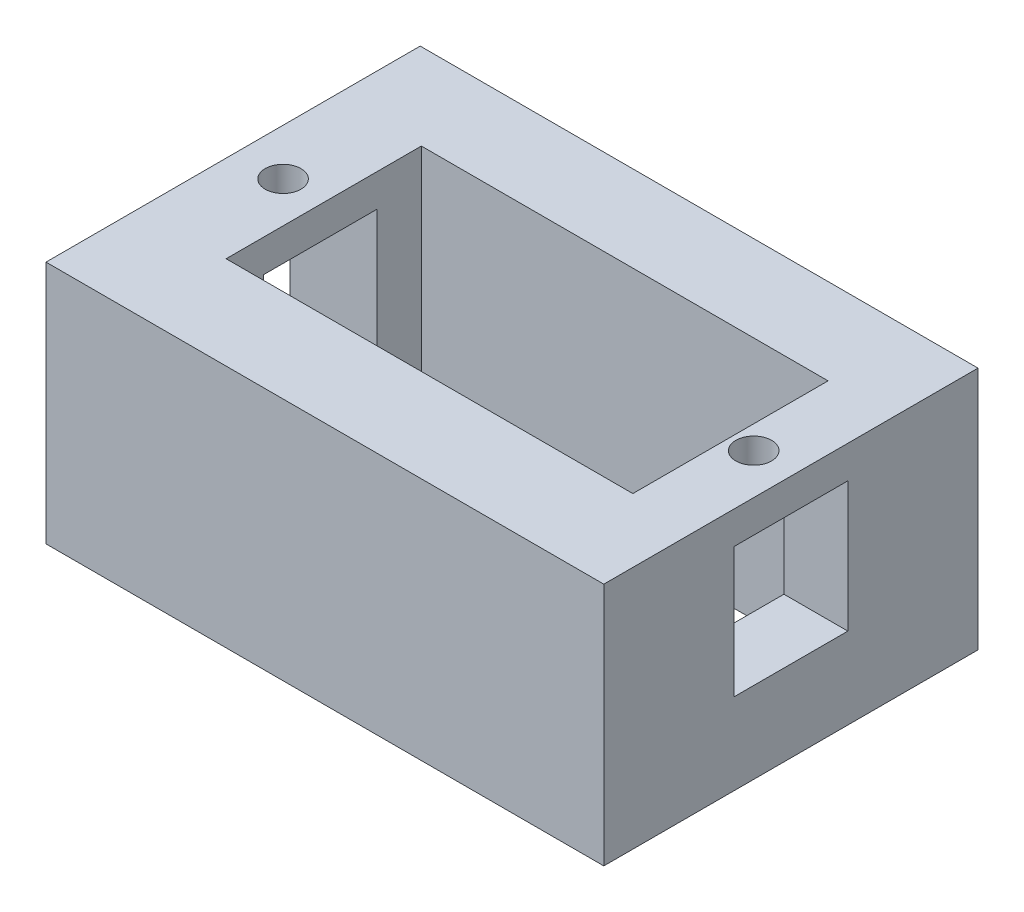
SolidWorks part; units mm, degrees
ref_plane "Plan de face" through (0, 0, 0) normal (0, 0, 1) x (1, 0, 0)
ref_plane "Plan de dessus" through (0, 0, 0) normal (0, 1, 0) x (1, 0, 0)
ref_plane "Plan de droite" through (0, 0, 0) normal (1, 0, 0) x (0, 0, -1)
sketch "Esquisse1" plane through (0, 0, 0) normal (0, 1, 0) x (1, 0, 0)
  line L0 (-6.3571, 7.25) -> (18.6429, 7.25)
  line L1 (-6.3571, 7.25) -> (-6.3571, -4.75)
  line L2 (18.6429, 7.25) -> (18.6429, -4.75)
  line L3 (-6.3571, -4.75) -> (18.6429, -4.75)
  line L4 (-11.7143, 12.5357) -> (22.5714, 12.5357)
  line L5 (-11.7143, 12.5357) -> (-11.7143, -10.4643)
  line L6 (22.5714, 12.5357) -> (22.5714, -10.4643)
  line L7 (-11.7143, -10.4643) -> (22.5714, -10.4643)
  dimension "D1" = 25
  dimension "D2" = 12
extrude "Boss.-Extru.1" add sketch "Esquisse1" along normal blind 15
sketch "Esquisse2" plane through (-11.7143, 0, 0) normal (-1, 0, 0) x (0, 0, 1)
  line L0 (-1.0357, 15) -> (-1.0357, 13)
  line L1 (-12.5357, 15) -> (10.4643, 15) construction
  line L2 (2.4643, 13) -> (-4.5357, 13)
  line L3 (2.4643, 13) -> (2.4643, 5)
  line L4 (2.4643, 5) -> (-4.5357, 5)
  line L5 (-4.5357, 5) -> (-4.5357, 13)
  point P6 (-1.0357, 13)
extrude "Enlèv. mat.-Extru.1" cut sketch "Esquisse2" against normal blind 60 contours L5 L4 L3 L2
sketch "Esquisse3" plane through (0, 15, 0) normal (0, 1, 0) x (1, 0, 0)
  line L0 (18.6429, 1.25) -> (22.5714, 1.25)
  line L1 (18.6429, -4.75) -> (18.6429, 7.25) construction
  line L2 (22.5714, -10.4643) -> (22.5714, 12.5357) construction
  line L3 (22.5714, 1.25) -> (17.5714, 1.25)
  line L4 (-6.3571, 1.25) -> (-11.3571, 1.25)
  line L7 (-6.3571, 7.25) -> (-6.3571, -4.75) construction
  circle A0 centre (-8.8571, 1.25) radius 1.1
  circle A1 centre (20.0714, 1.25) radius 1.1
extrude "Enlèv. mat.-Extru.2" cut sketch "Esquisse3" against normal blind 10 contours A0 | A1
